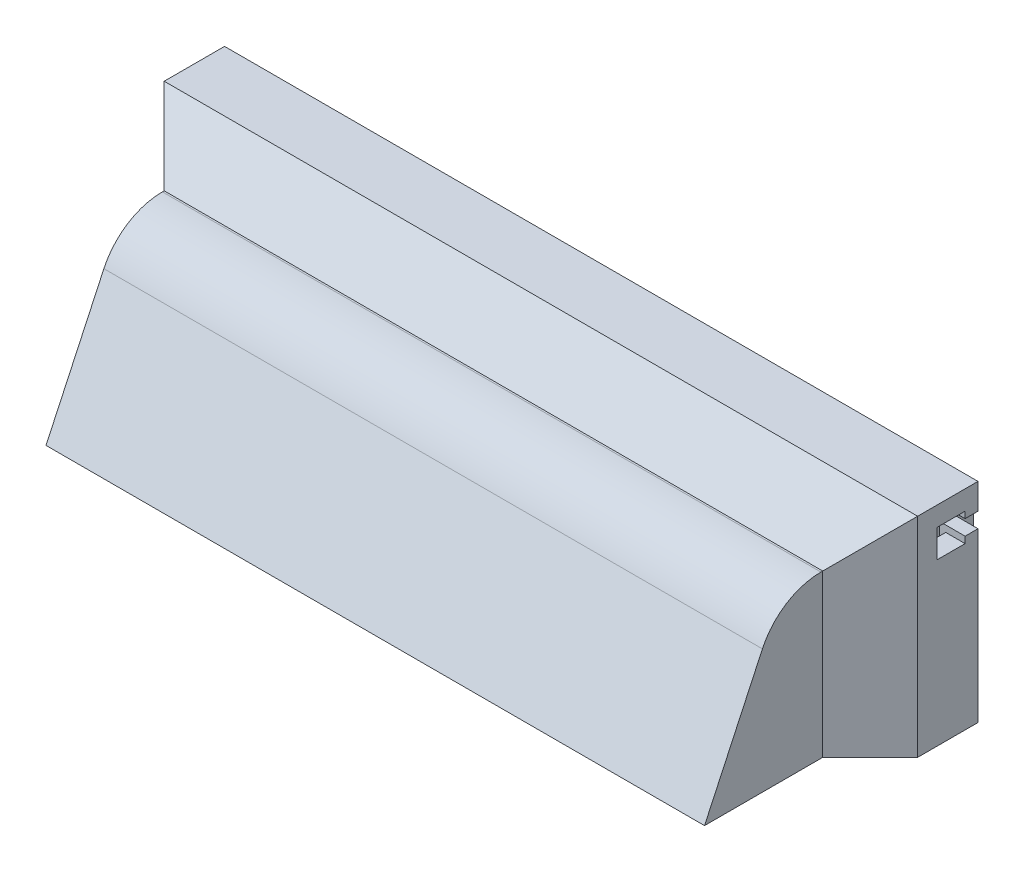
SolidWorks part; units mm, degrees
ref_plane "Front Plane" through (0, 0, 0) normal (0, 0, 1) x (1, 0, 0)
ref_plane "Top Plane" through (0, 0, 0) normal (0, 1, 0) x (1, 0, 0)
ref_plane "Right Plane" through (0, 0, 0) normal (1, 0, 0) x (0, 0, -1)
sketch "Sketch1" plane through (0, 0, 0) normal (0, 1, 0) x (1, 0, 0)
  line L1 (-51, -15) -> (51, -15)
  line L2 (-51, -15) -> (-51, 15)
  line L3 (-51, 15) -> (51, 15)
  line L4 (51, -15) -> (51, 15)
  line L5 (-51, -15) -> (51, 15) construction
  line L6 (-51, 15) -> (51, -15) construction
  point P0 (0, 0)
  dimension "D1" = 102
  dimension "D2" = 30
extrude "Boss-Extrude1" add sketch "Sketch1" along normal blind 25
sketch "Sketch2" plane through (0, 0, 0) normal (0, -1, 0) x (1, 0, 0)
  line L0 (51, -15) -> (-51, -15) construction
  line L1 (-46, -37) -> (46, -37)
  line L2 (-46, -37) -> (-46, 5)
  line L3 (-44, 7) -> (44, 7)
  line L4 (46, -37) -> (46, 5)
  line L5 (-46, -37) -> (46, 7) construction
  line L6 (-46, 7) -> (46, -37) construction
  line L7 (-51, 15) -> (51, 15) construction
  arc A0 (-44, 7) -> (-46, 5) centre (-44, 5) ccw
  arc A1 (46, 5) -> (44, 7) centre (44, 5) ccw
  point P0 (0, -15)
  dimension "D3" = 2
  dimension "D1" = 92
  dimension "D2" = 8
extrude "Cut-Extrude1" cut sketch "Sketch2" against normal blind 21
sketch "Sketch3" plane through (51, 0, 0) normal (1, 0, 0) x (0, 0, -1)
  line L0 (-15, 25) -> (-26.6577, 0)
  line L1 (-26.6577, 0) -> (-15, 0)
  line L2 (-15, 25) -> (-15, 0) construction
  line L3 (-15, 0) -> (-15, 25)
  dimension "D1" = 25
extrude "Boss-Extrude2" add sketch "Sketch3" against normal up to surface (102 mm away) up to face at (-51, 12.5, 0)
sketch "Sketch4" plane through (0, 0, 0) normal (0, -1, 0) x (1, 0, 0)
  line L0 (-30, 17) -> (30, 17) construction
  line L1 (0, 0) -> (0, 17) construction
  line L2 (44, 7) -> (-44, 7) construction
  circle A0 centre (-30, 17) radius 6.05
  circle A1 centre (30, 17) radius 6.05
  dimension "D1" = 12.1
  dimension "D2" = 12.1
  dimension "D3" = 60
  dimension "D4" = 10
extrude "Cut-Extrude2" cut sketch "Sketch4" against normal blind 3.5
fillet "Fillet1" radius 10 1 edges at (0, 25, 15)
sketch "Sketch5" plane through (0, 25, 0) normal (0, 1, 0) x (1, 0, 0)
  line L0 (-30, 26) -> (-30, 4) construction
  line L1 (51, 15) -> (-51, 15) construction
  line L2 (-24, 26) -> (-24, 4)
  line L3 (-36, 26) -> (-36, 4)
  line L4 (30, 4) -> (30, 26) construction
  line L5 (24, 4) -> (24, 26)
  line L6 (36, 4) -> (36, 26)
  line L7 (44, -7) -> (-44, -7) construction
  line L8 (44, -7) -> (-44, -7) construction
  arc A0 (-24, 26) -> (-36, 26) centre (-30, 26) ccw
  arc A1 (-36, 4) -> (-24, 4) centre (-30, 4) ccw
  arc A2 (24, 4) -> (36, 4) centre (30, 4) ccw
  arc A3 (36, 26) -> (24, 26) centre (30, 26) ccw
  point P4 (-30, 15)
  point P10 (30, 15)
  dimension "D3" = 6
  dimension "D4" = 6
  dimension "D1" = 30
  dimension "D2" = 30
  dimension "D5" = 11
  dimension "D6" = 11
extrude "Cut-Extrude3" cut sketch "Sketch5" against normal blind 23.5
sketch "Sketch6" plane through (0, 0, 0) normal (0, -1, 0) x (1, 0, 0)
  line L0 (51, -2) -> (55.35, -2)
  line L1 (51, 26.6577) -> (51, -15) construction
  line L2 (55.35, -2) -> (55.35, -6.35)
  line L3 (55.35, -6.35) -> (54.35, -6.35)
  line L4 (54.35, -6.35) -> (54.35, -8.35)
  line L5 (54.35, -8.35) -> (58.35, -8.35)
  line L6 (58.35, -8.35) -> (58.35, 1)
  line L7 (58.35, 1) -> (51, 8.35)
  line L8 (51, 8.35) -> (51, -2)
  line L9 (51, -6.35) -> (52, -6.35)
  line L10 (52, -6.35) -> (52, -8.35)
  line L11 (52, -8.35) -> (51, -8.35)
  line L12 (51, -8.35) -> (51, -6.35)
  line L13 (52, -6.35) -> (54.35, -6.35) construction
  line L14 (51, -15) -> (36, -15) construction
  dimension "D1" = 4.35
  dimension "D2" = 4.35
  dimension "D3" = 1
  dimension "D4" = 2
  dimension "D5" = 3
  dimension "D6" = 135
  dimension "D7" = 3
  dimension "D8" = 1
  dimension "D9" = 2
  dimension "D10" = 2
  dimension "D11" = 13
extrude "Boss-Extrude3" add sketch "Sketch6" against normal up to surface (25 mm away) up to face at (0, 25, -6.3951)
sketch "Sketch7" plane through (58.35, 0, 0) normal (1, 0, 0) x (0, 0, -1)
  line L0 (2, 25) -> (2, 29.35)
  line L1 (2, 29.35) -> (6.35, 29.35)
  line L2 (6.35, 29.35) -> (6.35, 28.35)
  line L3 (6.35, 28.35) -> (8.35, 28.35)
  line L4 (8.35, 28.35) -> (8.35, 32.35)
  line L5 (8.35, 32.35) -> (-1, 32.35)
  line L6 (-1, 32.35) -> (-8.35, 25)
  line L7 (-8.35, 25) -> (2, 25)
  line L8 (6.35, 25) -> (6.35, 26)
  line L9 (6.35, 26) -> (8.35, 26)
  line L10 (8.35, 26) -> (8.35, 25)
  line L11 (8.35, 25) -> (6.35, 25)
  line L12 (6.35, 26) -> (6.35, 28.35) construction
  dimension "D1" = 4.35
  dimension "D2" = 4.35
  dimension "D3" = 1
  dimension "D4" = 2
  dimension "D5" = 3
  dimension "D6" = 135
  dimension "D7" = 3
  dimension "D8" = 1
  dimension "D9" = 2
  dimension "D10" = 0
  dimension "D11" = 0
extrude "Boss-Extrude4" add sketch "Sketch7" against normal offset from surface (116.7 mm away) 7.35 up to face at (-51, 14.1094, 4.7642) offset beyond the face yes
sketch "Sketch8" plane through (0, 25, 0) normal (0, -1, 0) x (1, 0, 0)
  line L0 (58.35, 8.35) -> (51, 8.35)
  line L1 (51, 8.35) -> (58.35, 1)
  line L2 (58.35, 1) -> (58.35, 8.35)
extrude "Cut-Extrude4" cut sketch "Sketch8" against normal blind 7.35
mirror "Mirror1" about plane through (0, 0, 0) normal (1, 0, 0) of "Cut-Extrude4", "Boss-Extrude3"
sketch "Sketch9" plane through (0, 0, -8.35) normal (0, 0, -1) x (-1, 0, 0)
  line L0 (54.35, 25) -> (54.35, 26)
  line L1 (58.35, 26) -> (-58.35, 26) construction
  line L3 (54.35, 26) -> (52, 26)
  line L4 (54.35, 26) -> (54.35, 25)
  line L5 (54.35, 25) -> (52, 25)
  line L6 (52, 26) -> (52, 25)
  line L7 (36, 25) -> (24, 25)
  line L8 (36, 25) -> (36, 26)
  line L9 (36, 26) -> (24, 26)
  line L10 (24, 25) -> (24, 26)
  line L11 (-24, 25) -> (-36, 25)
  line L12 (-24, 25) -> (-24, 26)
  line L13 (-24, 26) -> (-36, 26)
  line L14 (-36, 25) -> (-36, 26)
  line L15 (-52, 25) -> (-54.35, 25)
  line L16 (-52, 25) -> (-52, 26)
  line L17 (-52, 26) -> (-54.35, 26)
  line L18 (-54.35, 25) -> (-54.35, 26)
  line M4 (-54.35, 25) -> (-52, 25)
  line M9 (-36, 25) -> (-24, 25)
  line M16 (52, 25) -> (54.35, 25)
  line M20 (58.35, 26) -> (-58.35, 26)
  dimension "D1" = 12
  dimension "D2" = 12
extrude "Cut-Extrude5" cut sketch "Sketch9" against normal blind 3 contours L18 L16 M4 M20 | L14 L12 M9 M20 | L6 L0 M20 M16 | L9 L10 L7 L8
equation "\"D4@Sketch5\"=\"D3@Sketch5\""
